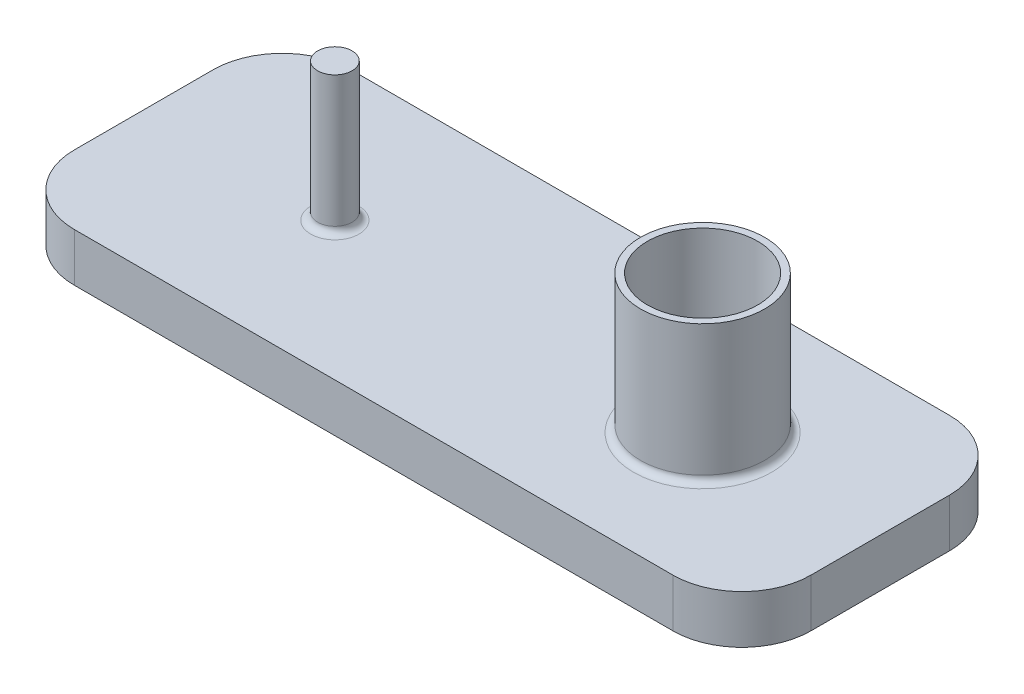
SolidWorks part; units mm, degrees
material "1023 Carbon Steel Sheet (SS)"
ref_plane "Front Plane" through (0, 0, 0) normal (0, 0, 1) x (1, 0, 0)
ref_plane "Top Plane" through (0, 0, 0) normal (0, 1, 0) x (1, 0, 0)
ref_plane "Right Plane" through (0, 0, 0) normal (1, 0, 0) x (0, 0, -1)
sketch "Sketch1" plane through (0, 0, 0) normal (0, 1, 0) x (1, 0, 0)
  line L1 (-61.391, -32.8689) -> (25.3393, -32.8689)
  line L2 (-71.391, -22.8689) -> (-71.391, -2.78)
  line L3 (-61.391, 7.22) -> (25.3393, 7.22)
  line L4 (35.3393, -22.8689) -> (35.3393, -2.78)
  line L5 (-71.391, -32.8689) -> (35.3393, 7.22) construction
  line L6 (-71.391, 7.22) -> (35.3393, -32.8689) construction
  arc A0 (35.3393, -2.78) -> (25.3393, 7.22) centre (25.3393, -2.78) ccw
  arc A1 (25.3393, -32.8689) -> (35.3393, -22.8689) centre (25.3393, -22.8689) ccw
  arc A2 (-71.391, -22.8689) -> (-61.391, -32.8689) centre (-61.391, -22.8689) ccw
  arc A3 (-71.391, -2.78) -> (-61.391, 7.22) centre (-61.391, -2.78) cw
  point P0 (-18.0258, -12.8244)
  dimension "D1" = 10
extrude "Boss-Extrude1" add sketch "Sketch1" along normal blind 7
sketch "Sketch2" plane through (0, 7, 0) normal (0, 1, 0) x (1, 0, 0)
  circle A0 centre (-43.6937, -12.8244) radius 2.5
  circle A1 centre (9.5915, -12.8244) radius 8
  circle A2 centre (9.5915, -12.8244) radius 9
  dimension "D1" = 5
  dimension "D2" = 16
  dimension "D3" = 18
extrude "Boss-Extrude2" add sketch "Sketch2" along normal blind 20
fillet "Fillet1" radius 1 2 edges at (9.5915, 7, 21.8244) (-43.6937, 7, 15.3244)
scale "Scale1" scale about origin uniform scaling yes scale factor 5
